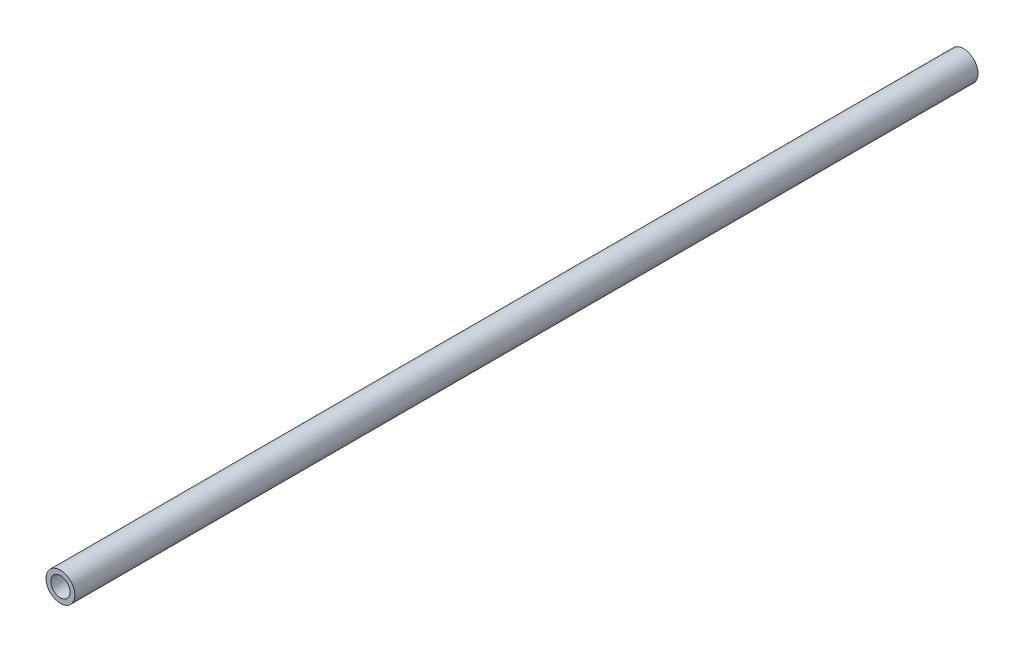
SolidWorks part; units mm, degrees
ref_plane "Front Plane" through (0, 0, 0) normal (0, 0, 1) x (1, 0, 0)
ref_plane "Top Plane" through (0, 0, 0) normal (0, 1, 0) x (1, 0, 0)
ref_plane "Right Plane" through (0, 0, 0) normal (1, 0, 0) x (0, 0, -1)
sketch "Sketch1" plane through (0, 0, 0) normal (0, 0, 1) x (1, 0, 0)
  circle A0 centre (390.7614, 31.0815) radius 7.5
  circle A1 centre (390.7614, 31.0815) radius 5
extrude "Boss-Extrude1" add sketch "Sketch1" along normal blind 470
